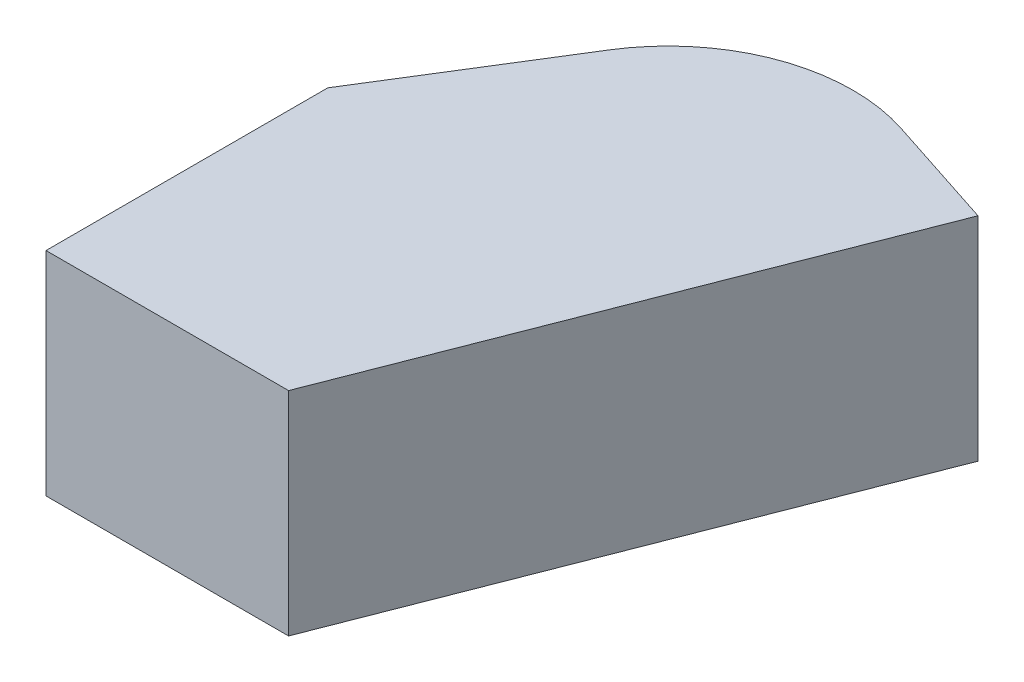
SolidWorks part; units mm, degrees
material "Pure Gold"
ref_plane "Front Plane" through (0, 0, 0) normal (0, 0, 1) x (1, 0, 0)
ref_plane "Top Plane" through (0, 0, 0) normal (0, 1, 0) x (1, 0, 0)
ref_plane "Right Plane" through (0, 0, 0) normal (1, 0, 0) x (0, 0, -1)
sketch "Sketch1" plane through (0, 0, 0) normal (0, 1, 0) x (1, 0, 0)
  line L0 (-66.6738, 0) -> (-37.0678, 47.6333)
  line L1 (0, 0) -> (-66.6738, 0) construction
  line L2 (0, 0) -> (0, -77.4519) construction
  line L3 (0, -77.4519) -> (-66.6738, -77.4519)
  line L4 (-66.6738, 0) -> (-66.6738, -77.4519)
  line L5 (21.8265, 69.1139) -> (53.1385, 58.9035)
  line L6 (53.1385, 58.9035) -> (0, -77.4519)
  arc A0 (-37.0678, 47.6333) -> (21.8265, 69.1139) centre (6.0775, 20.8169) cw
  point P5 (-16.0418, 81.4623)
  dimension "D1" = 50.8
extrude "Boss-Extrude1" add sketch "Sketch1" along normal blind 58.42
